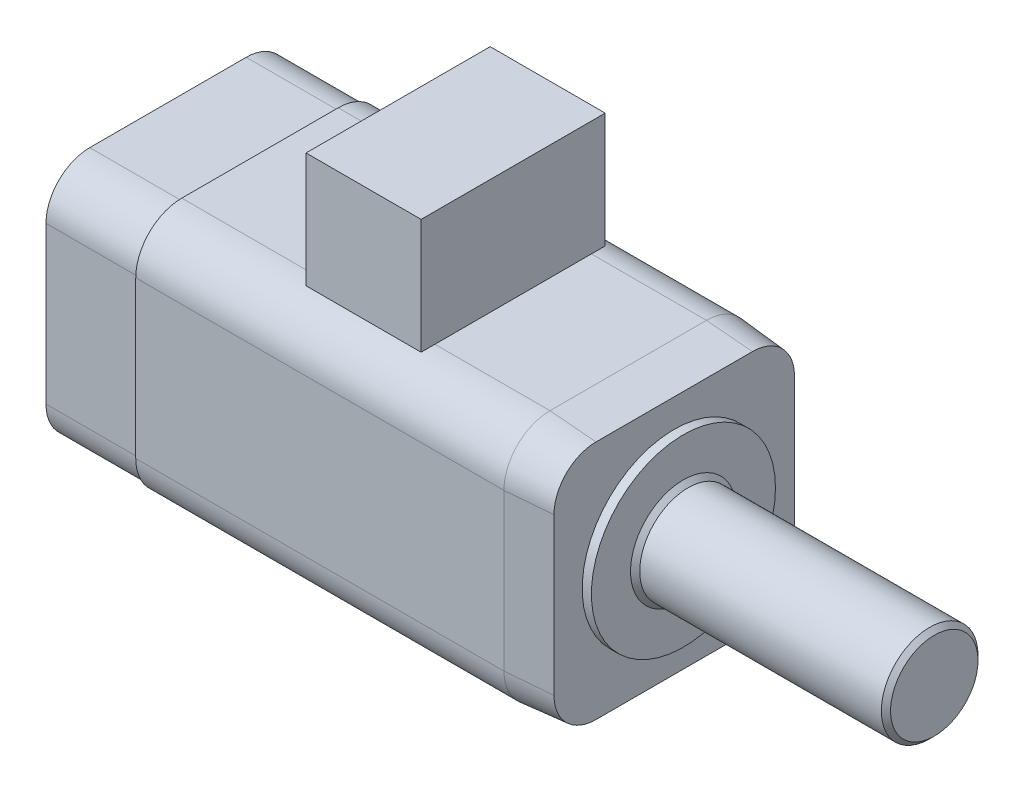
SolidWorks part; units mm, degrees
ref_plane "前基準面" through (0, 0, 0) normal (0, 0, 1) x (1, 0, 0)
ref_plane "上基準面" through (0, 0, 0) normal (0, 1, 0) x (1, 0, 0)
ref_plane "右基準面" through (0, 0, 0) normal (1, 0, 0) x (0, 0, -1)
sketch "草圖1" plane through (0, 0, 0) normal (1, 0, 0) x (0, 0, -1)
  line L0 (0, 17.9092) -> (0, 0) construction
  line L1 (-34, 54) -> (34, 54)
  line L2 (-54, 34) -> (-54, -34)
  line L3 (-34, -54) -> (34, -54)
  line L4 (54, 34) -> (54, -34)
  line L5 (0, 0) -> (24.0556, 0) construction
  arc A0 (54, 34) -> (34, 54) centre (34, 34) ccw
  arc A1 (-54, 34) -> (-34, 54) centre (-34, 34) cw
  arc A2 (-34, -54) -> (-54, -34) centre (-34, -34) cw
  arc A3 (54, -34) -> (34, -54) centre (34, -34) cw
  dimension "D2" = 20
  dimension "D1" = 108
extrude "伸長1" add sketch "草圖1" along normal blind 20 draft 5
sketch "草圖2" plane through (20, 0, 0) normal (1, 0, 0) x (0, 0, -1)
  circle A0 centre (0, 0) radius 40
  dimension "D1" = 80
extrude "伸長2" add sketch "草圖2" along normal blind 4
sketch "草圖3" plane through (24, 0, 0) normal (1, 0, 0) x (0, 0, -1)
  circle A0 centre (0, 0) radius 21
  dimension "D1" = 42
extrude "伸長3" add sketch "草圖3" along normal blind 109
chamfer "導角1" distance 2 angle 45 1 edges at (24, 0, -21)
ref_plane "平面1" through (0, 0, 16) normal (0, 0, 1) x (1, 0, 0)
sketch "草圖4" plane through (0, 0, 16) normal (0, 0, 1) x (1, 0, 0)
  line L0 (133, 0) -> (49, 0) construction
  line L1 (133, -21) -> (133, 21) construction
  line L2 (133, 6) -> (49, 6)
  line L3 (133, -6) -> (49, -6)
  line L4 (133, 6) -> (133, -6)
  arc A0 (49, 6) -> (49, -6) centre (49, 0) ccw
  dimension "D1" = 90
  dimension "D2" = 6
  dimension "D3" = 6
extrude "除料-伸長1" [suppressed] cut sketch "草圖4" along normal up to next
sketch "草圖5" [suppressed] plane through (0, 0, 16) normal (0, 0, 1) x (1, 0, 0)
  line L3 (133, -6) -> (133, 6)
  line L4 (133, 6) -> (49, 6)
  line L5 (49, -6) -> (133, -6)
  line L6 (133, -6) -> (133, 6)
  line L7 (133, 6) -> (49, 6)
  line L8 (49, -6) -> (133, -6)
  arc A1 (49, 6) -> (49, -6) centre (49, 0) ccw
  arc A2 (49, 6) -> (49, -6) centre (49, 0) ccw
  dimension "D1" = 0
extrude "伸長4" [suppressed] add sketch "草圖5" along normal blind 8 separate body
chamfer "導角2" distance 2 angle 45 1 edges at (133, 0, -21)
sketch "草圖6" plane through (0, 0, 0) normal (-1, 0, 0) x (0, 0, 1)
  line L4 (-54, 34) -> (-54, -34)
  line L5 (-34, -54) -> (34, -54)
  line L6 (54, -34) -> (54, 34)
  line L7 (34, 54) -> (-34, 54)
  line L8 (-54, 34) -> (-54, -34)
  line L9 (-34, -54) -> (34, -54)
  line L10 (54, -34) -> (54, 34)
  line L11 (34, 54) -> (-34, 54)
  arc A4 (-34, 54) -> (-54, 34) centre (-34, 34) ccw
  arc A5 (-54, -34) -> (-34, -54) centre (-34, -34) ccw
  arc A6 (34, -54) -> (54, -34) centre (34, -34) ccw
  arc A7 (54, 34) -> (34, 54) centre (34, 34) ccw
  arc A8 (-34, 54) -> (-54, 34) centre (-34, 34) ccw
  arc A9 (-54, -34) -> (-34, -54) centre (-34, -34) ccw
  arc A10 (34, -54) -> (54, -34) centre (34, -34) ccw
  arc A11 (54, 34) -> (34, 54) centre (34, 34) ccw
  dimension "D1" = 0
extrude "伸長5" add sketch "草圖6" along normal blind 160
sketch "草圖7" plane through (0, 54, 0) normal (0, 1, 0) x (1, 0, 0)
  line L0 (-127.8223, 0) -> (-345.0945, 0) construction
  line L1 (-100, 40) -> (-50, 40)
  line L2 (-100, 40) -> (-100, -40)
  line L3 (-100, -40) -> (-50, -40)
  line L4 (-50, 40) -> (-50, -40)
  line L5 (-160, -34) -> (-160, 34) construction
  dimension "D1" = 80
  dimension "D2" = 60
  dimension "D3" = 50
extrude "伸長6" add sketch "草圖7" along normal blind 50
sketch "草圖8" plane through (-160, 0, 0) normal (-1, 0, 0) x (0, 0, 1)
  line L8 (-53, 34) -> (-53, -34)
  line L9 (-34, -53) -> (34, -53)
  line L10 (53, -34) -> (53, 34)
  line L11 (34, 53) -> (-34, 53)
  line L12 (-53, 34) -> (-53, -34)
  line L13 (-34, -53) -> (34, -53)
  line L14 (53, -34) -> (53, 34)
  line L15 (34, 53) -> (-34, 53)
  arc A8 (-34, 53) -> (-53, 34) centre (-34, 34) ccw
  arc A9 (-53, -34) -> (-34, -53) centre (-34, -34) ccw
  arc A10 (34, -53) -> (53, -34) centre (34, -34) ccw
  arc A11 (53, 34) -> (34, 53) centre (34, 34) ccw
  arc A12 (-34, 53) -> (-53, 34) centre (-34, 34) ccw
  arc A13 (-53, -34) -> (-34, -53) centre (-34, -34) ccw
  arc A14 (34, -53) -> (53, -34) centre (34, -34) ccw
  arc A15 (53, 34) -> (34, 53) centre (34, 34) ccw
  dimension "D1" = 1
extrude "伸長7" add sketch "草圖8" along normal blind 40
